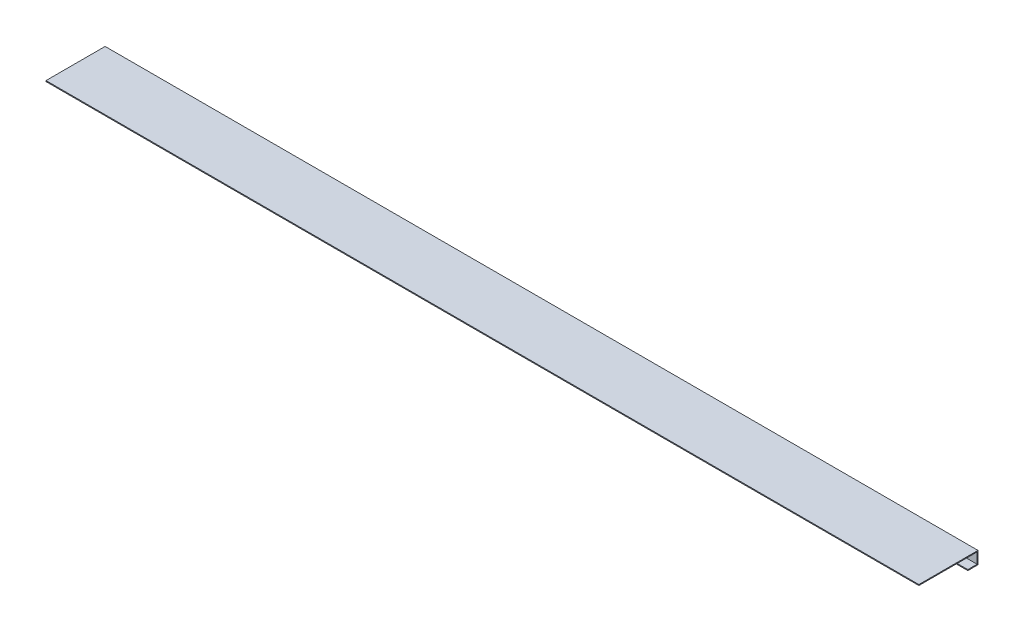
SolidWorks part; units mm, degrees
ref_plane "Front Plane" through (0, 0, 0) normal (0, 0, 1) x (1, 0, 0)
ref_plane "Top Plane" through (0, 0, 0) normal (0, 1, 0) x (1, 0, 0)
ref_plane "Right Plane" through (0, 0, 0) normal (1, 0, 0) x (0, 0, -1)
sketch "Sketch1" plane through (0, 0, 0) normal (1, 0, 0) x (0, 0, -1)
  line L0 (0, 0) -> (128, 0)
  line L1 (128, 0) -> (128, -27)
  line L2 (128, -27) -> (106, -27)
  line L3 (0, -2) -> (126, -2)
  line L4 (126, -2) -> (126, -25)
  line L5 (126, -25) -> (106, -25)
  line L6 (0, 0) -> (0, -2)
  line L7 (106, -27) -> (106, -25)
  dimension "D1" = 2
  dimension "D2" = 128
  dimension "D3" = 27
  dimension "D4" = 22
extrude "Boss-Extrude1" add sketch "Sketch1" along normal blind 1890
equation "\"door_base_long7_R1_L_open_Single_height\"=1890.0"
equation "\"D1@Boss-Extrude1\"=\"door_base_long7_R1_L_open_Single_height\""
equation "\"CarBeamWidth\"=700.0"
equation "\"WheelWidth\"=650.0"
equation "\"Wheel_FrontBoxDistance\"=1390.0"
equation "\"MetalSheet_3mm_length\"=5030.0"
equation "\"MetalSheet_3mm_width\"=1923.0"
equation "\"MetalSheet_3mm_FloorCut_L_length\"=1764.0"
equation "\"MetalSheet_3mm_FloorCut_L_disdance\"=1665.0"
equation "\"MetalSheet_3mm_FloorCut_R_length\"=1764.0"
equation "\"MetalSheet_3mm_FloorCut_R_disdance\"=1665.0"
equation "\"indoorHeight\"=1940.0"
equation "\"haveDoor_R\"=1"
equation "\"side_door_bottom_R_3mm_length\"=1934.0"
equation "\"1Bar_Side_RF_3mm_length\"=1493.0"
equation "\"1Bar_Side_RB_3mm_length\"=1493.0"
equation "\"DoorSeparator_RF_3mm_withHinge_toFrontDistance\"=1673.0"
equation "\"DoorSeparator_RF_3mm_withHinge_exist\"=1"
equation "\"DoorSeparator_RB_3mm_withHinge_toFrontDistance\"=3427.0"
equation "\"DoorSeparator_RB_3mm_withHinge_exist\"=1"
equation "\"Door_R1_L_open_Single_toFrontDistance\"=2547.5"
equation "\"Door_R1_L_open_Single_exist\"=1"
equation "\"door_base_short7_R1_L_open_Single_height\"=1890.0"
equation "\"door_base_short7_R1_L_open_Single_width\"=864"
equation "\"Door_R1_R_open_Single_toFrontDistance\"=3422.0"
equation "\"Door_R1_R_open_Single_exist\"=1"
equation "\"door_base_long7_R1_R_open_Single_height\"=1890.0"
equation "\"door_base_short7_R1_R_open_Single_height\"=1890.0"
equation "\"door_base_short7_R1_R_open_Single_width\"=864"
equation "\"x\"=66.0"
equation "\"da\"=62.0"
equation "\"SquareTube_length\"=1923.0"
equation "\"channelSteel_length\"=5030.0"
equation "\"SquareTube_inFront_AvgDistance\"=285.0"
equation "\"SquareTube_inFront_TotalCount\"=5"
equation "\"SquareTube_inFront1_cutDepth50_R\"=0.5"
equation "\"SquareTube_inFront1_cutDepth50_L\"=0.5"
equation "\"SquareTube_inFront2_cutDepth50_R\"=0.5"
equation "\"SquareTube_inFront2_cutDepth50_L\"=0.5"
equation "\"SquareTube_inFront3_cutDepth50_R\"=0.5"
equation "\"SquareTube_inFront3_cutDepth50_L\"=0.5"
equation "\"SquareTube_inFront4_cutDepth50_R\"=0.5"
equation "\"SquareTube_inFront4_cutDepth50_L\"=0.5"
equation "\"SquareTube_inFront5_cutDepth50_R\"=50"
equation "\"SquareTube_inFront5_cutDepth50_L\"=50"
equation "\"SquareTube_inFront6_cutDepth50_R\"=50"
equation "\"SquareTube_inFront6_cutDepth50_L\"=50"
equation "\"SquareTube_inFront7_cutDepth50_R\"=50"
equation "\"SquareTube_inFront7_cutDepth50_L\"=50"
equation "\"SquareTube_inFront8_cutDepth50_R\"=50"
equation "\"SquareTube_inFront8_cutDepth50_L\"=50"
equation "\"SquareTube_inFront9_cutDepth50_R\"=50"
equation "\"SquareTube_inFront9_cutDepth50_L\"=50"
equation "\"SquareTube_inFront10_cutDepth50_R\"=50"
equation "\"SquareTube_inFront10_cutDepth50_L\"=50"
equation "\"SquareTube_inFront11_cutDepth50_R\"=50"
equation "\"SquareTube_inFront11_cutDepth50_L\"=50"
equation "\"SquareTube_inFront12_cutDepth50_R\"=50"
equation "\"SquareTube_inFront12_cutDepth50_L\"=50"
equation "\"SquareTube_inFront13_cutDepth50_R\"=50"
equation "\"SquareTube_inFront13_cutDepth50_L\"=50"
equation "\"SquareTube_inFront14_cutDepth50_R\"=50"
equation "\"SquareTube_inFront14_cutDepth50_L\"=50"
equation "\"SquareTube_inBack_AvgDistance\"=333.125"
equation "\"SquareTube_inBack_TotalCount\"=9"
equation "\"SquareTube_inBack1_cutDepth50_R\"=50"
equation "\"SquareTube_inBack1_cutDepth50_L\"=50"
equation "\"SquareTube_inBack2_cutDepth50_R\"=50"
equation "\"SquareTube_inBack2_cutDepth50_L\"=50"
equation "\"SquareTube_inBack3_cutDepth50_R\"=50"
equation "\"SquareTube_inBack3_cutDepth50_L\"=50"
equation "\"SquareTube_inBack4_cutDepth50_R\"=50"
equation "\"SquareTube_inBack4_cutDepth50_L\"=50"
equation "\"SquareTube_inBack5_cutDepth50_R\"=50"
equation "\"SquareTube_inBack5_cutDepth50_L\"=50"
equation "\"SquareTube_inBack6_cutDepth50_R\"=0.5"
equation "\"SquareTube_inBack6_cutDepth50_L\"=0.5"
equation "\"SquareTube_inBack7_cutDepth50_R\"=0.5"
equation "\"SquareTube_inBack7_cutDepth50_L\"=0.5"
equation "\"SquareTube_inBack8_cutDepth50_R\"=0.5"
equation "\"SquareTube_inBack8_cutDepth50_L\"=0.5"
